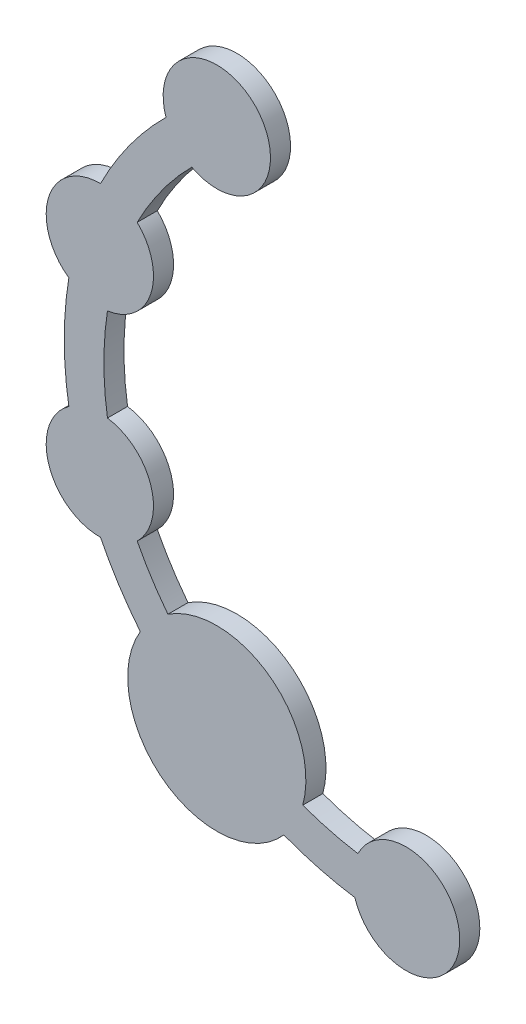
SolidWorks part; units mm, degrees
ref_plane "Front Plane" through (0, 0, 0) normal (0, 0, 1) x (1, 0, 0)
ref_plane "Top Plane" through (0, 0, 0) normal (0, 1, 0) x (1, 0, 0)
ref_plane "Right Plane" through (0, 0, 0) normal (1, 0, 0) x (0, 0, -1)
sketch "Sketch1" plane through (0, 0, 0) normal (0, 0, 1) x (1, 0, 0)
  line L0 (0, 0) -> (0, -32.53) construction
  line L1 (0, 0) -> (-19.1207, -26.3173) construction
  circle A0 centre (0, 0) radius 32.53 construction
  circle A1 centre (0, -32.53) radius 5.42
  circle A2 centre (-19.1207, -26.3173) radius 5.42
  circle A3 centre (-30.9379, -10.0523) radius 5.42
  circle A4 centre (-30.9379, 10.0523) radius 5.42
  circle A5 centre (-19.1207, 26.3173) radius 5.42
  dimension "D1" = 65.06
  dimension "D2" = 10.84
  dimension "D4" = 36
  dimension "D3" = 5
extrude "Boss-Extrude1" add sketch "Sketch1" along normal blind 2.03
sketch "Sketch2" plane through (0, 0, 2.03) normal (0, 0, 1) x (1, 0, 0)
  line L0 (0, 0) -> (0, -32.53) construction
  line L1 (-20.2962, 27.9354) -> (-17.9451, 24.6993)
  line L2 (0, -30.53) -> (0, -34.53)
  line L3 (-17.9451, 24.6993) -> (0, 0) construction
  arc A0 (0, -30.53) -> (-17.9451, 24.6993) centre (0, 0) cw
  arc A1 (0, -34.53) -> (-20.2962, 27.9354) centre (0, 0) cw
  circle A2 centre (0, 0) radius 32.53 construction
  point P8 (-19.1207, 26.3173)
  dimension "D1" = 2
extrude "Boss-Extrude2" add sketch "Sketch2" against normal blind 2.03
sketch "Sketch3" plane through (0, 0, 2.03) normal (0, 0, 1) x (1, 0, 0)
  circle A0 centre (-19.1207, -26.3173) radius 9
  dimension "D1" = 18
extrude "Boss-Extrude3" add sketch "Sketch3" against normal blind 2.03
